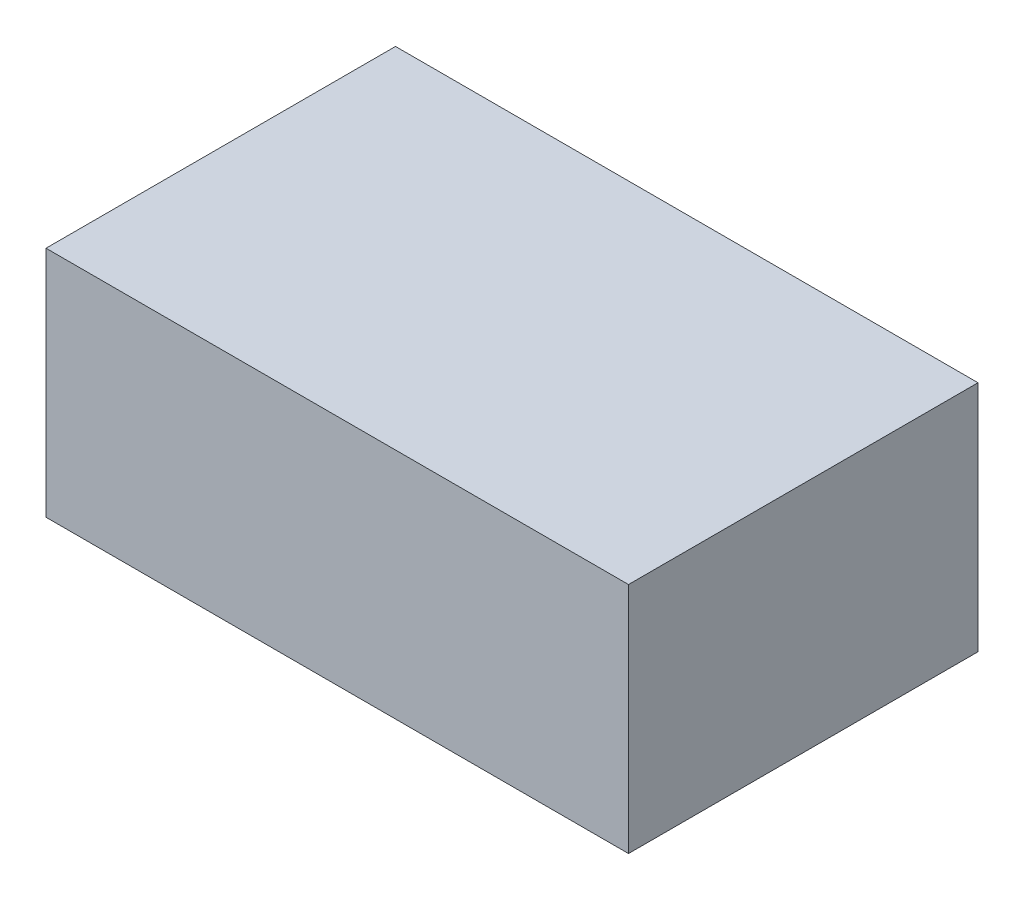
SolidWorks part; units mm, degrees
ref_plane "Front Plane" through (0, 0, 0) normal (0, 0, 1) x (1, 0, 0)
ref_plane "Top Plane" through (0, 0, 0) normal (0, 1, 0) x (1, 0, 0)
ref_plane "Right Plane" through (0, 0, 0) normal (1, 0, 0) x (0, 0, -1)
sketch "Sketch1" plane through (0, 0, 0) normal (0, 1, 0) x (1, 0, 0)
  line L1 (-127, 76.2) -> (127, 76.2)
  line L2 (-127, 76.2) -> (-127, -76.2)
  line L3 (-127, -76.2) -> (127, -76.2)
  line L4 (127, 76.2) -> (127, -76.2)
  line L5 (-127, 76.2) -> (127, -76.2) construction
  line L6 (-127, -76.2) -> (127, 76.2) construction
  point P0 (0, 0)
  dimension "D1" = 152.4
  dimension "D2" = 254
extrude "Boss-Extrude1" add sketch "Sketch1" along normal blind 101.6
